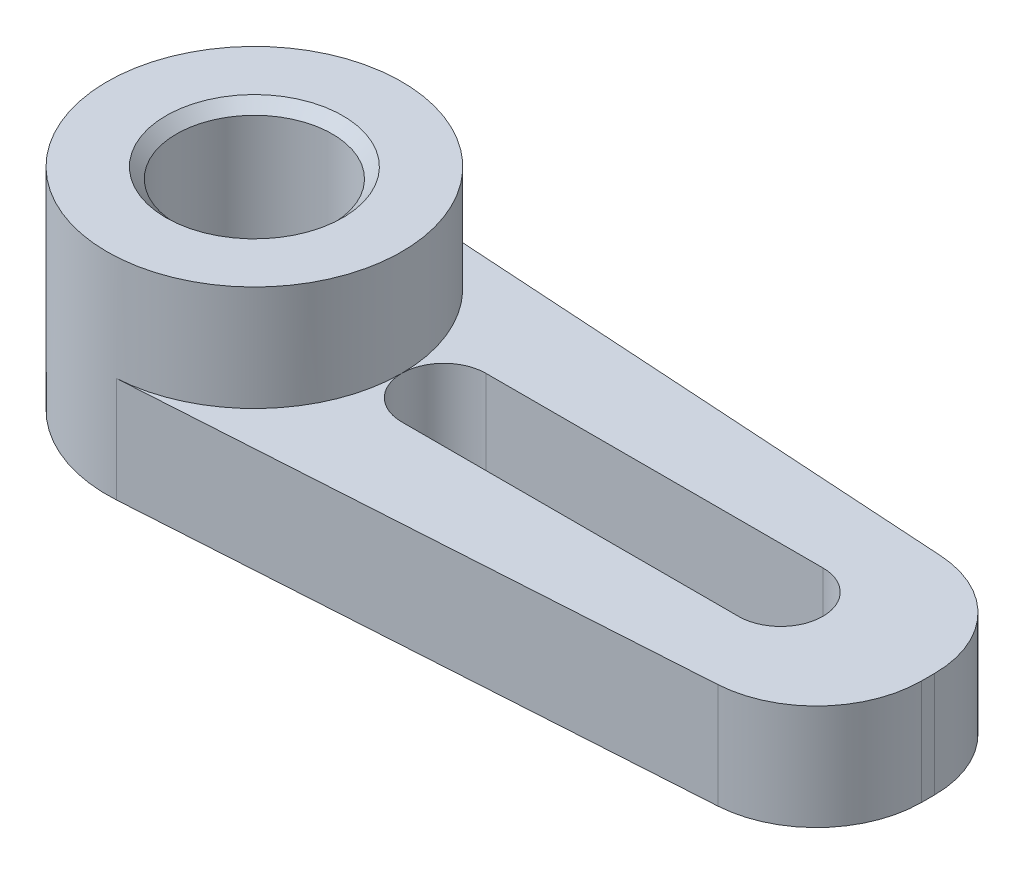
SolidWorks part; units mm, degrees
ref_plane "Front Plane" through (0, 0, 0) normal (0, 0, 1) x (1, 0, 0)
ref_plane "Top Plane" through (0, 0, 0) normal (0, 1, 0) x (1, 0, 0)
ref_plane "Right Plane" through (0, 0, 0) normal (1, 0, 0) x (0, 0, -1)
sketch "Sketch1" plane through (0, 0, 0) normal (0, 1, 0) x (1, 0, 0)
  line L0 (0, 0) -> (16, 0) construction
  line L1 (0.2198, 3.4931) -> (16, 2.5)
  line L2 (16, 2.5) -> (16, -2.5)
  line L3 (0.2198, -3.4931) -> (16, -2.5)
  circle A0 centre (0, 0) radius 1.25
  circle A1 centre (0, 0) radius 3.5
  point P7 (13.0026, 0)
  dimension "D1" = 2.5
  dimension "D2" = 7
  dimension "D3" = 5
  dimension "D4" = 16
extrude "Boss-Extrude1" add sketch "Sketch1" along normal blind 2.5
sketch "Sketch2" plane through (0, 2.5, 0) normal (0, 1, 0) x (1, 0, 0)
  circle A0 centre (0, 0) radius 3.5
  arc A1 (0.2198, 3.4931) -> (0.2198, -3.4931) centre (0, 0) ccw construction
  circle A4 centre (0, 0) radius 1.25
  circle A5 centre (0, 0) radius 1.25
  dimension "D1" = 0
extrude "Boss-Extrude2" add sketch "Sketch2" along normal blind 2.5
sketch "Sketch3" plane through (0, 5, 0) normal (0, 1, 0) x (1, 0, 0)
  circle A2 centre (0, 0) radius 1.85
  circle A3 centre (0, 0) radius 1.85
  circle A5 centre (0, 0) radius 1.25
  circle A6 centre (0, 0) radius 1.25
  dimension "D1" = 0.6
  dimension "D2" = 0
extrude "Cut-Extrude1" cut sketch "Sketch3" against normal blind 3
chamfer "Chamfer1" distance 0.25 angle 45 1 edges at (0, 5, 1.85)
sketch "Sketch4" plane through (0, 2.5, 0) normal (0, 1, 0) x (1, 0, 0)
  line L0 (4.5, 0) -> (12.5, 0) construction
  line L1 (4.5, 1) -> (12.5, 1)
  line L2 (4.5, -1) -> (12.5, -1)
  arc A0 (4.5, 1) -> (4.5, -1) centre (4.5, 0) ccw
  arc A1 (12.5, -1) -> (12.5, 1) centre (12.5, 0) ccw
  point P2 (8.5, 0)
  dimension "D1" = 8
  dimension "D2" = 2
  dimension "D3" = 8.5
extrude "Cut-Extrude2" cut sketch "Sketch4" against normal blind 3
fillet "Fillet1" radius 2.5 2 edges at (16, 1.25, 2.5) (16, 1.25, -2.5)
